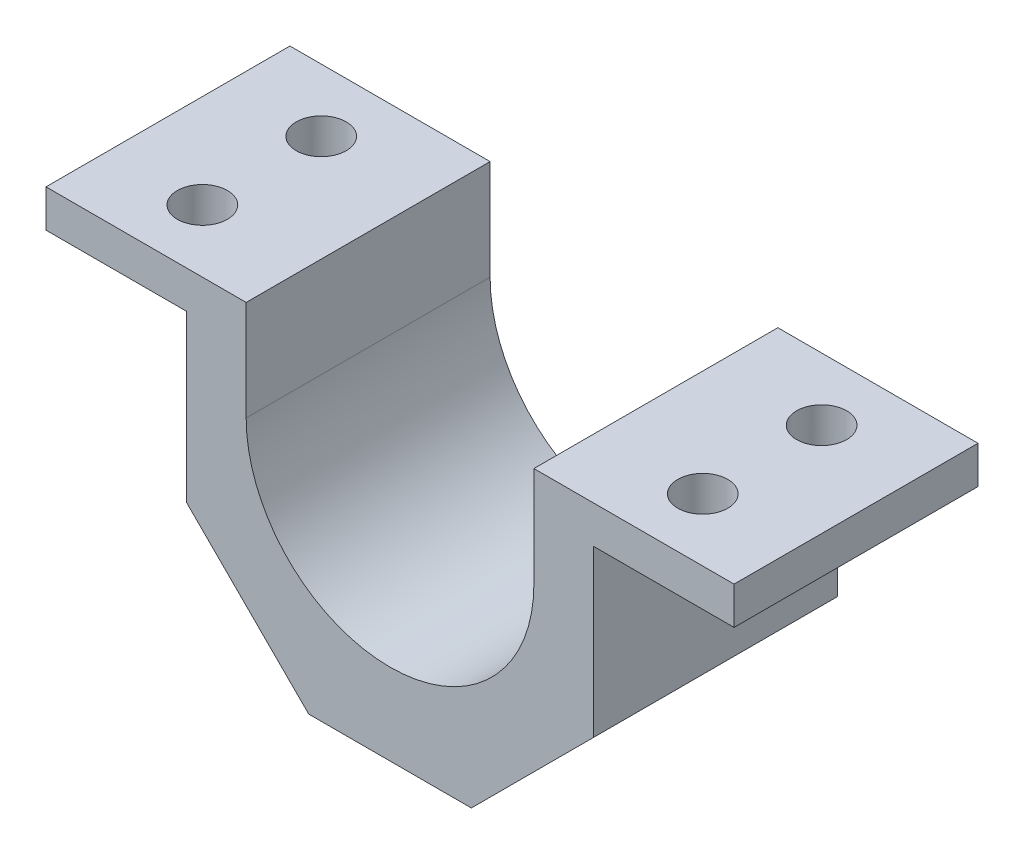
SolidWorks part; units mm, degrees
ref_plane "Front Plane" through (0, 0, 0) normal (0, 0, 1) x (1, 0, 0)
ref_plane "Top Plane" through (0, 0, 0) normal (0, 1, 0) x (1, 0, 0)
ref_plane "Right Plane" through (0, 0, 0) normal (1, 0, 0) x (0, 0, -1)
sketch "Sketch1" plane through (0, 0, 0) normal (0, 0, 1) x (1, 0, 0)
  line L0 (0, -73.4149) -> (0, 69.1816) construction
  line L4 (55, 10) -> (32.5, 10)
  line L5 (32.5, 10) -> (32.5, -16.5)
  line L6 (32.5, -16.5) -> (13, -36)
  line L7 (13, -36) -> (-13, -36)
  line L8 (-32.5, -16.5) -> (-13, -36)
  line L9 (-32.5, 10) -> (-32.5, -16.5)
  line L10 (-55, 16) -> (-55, 10)
  line L11 (-55, 10) -> (-32.5, 10)
  line L12 (-23, 16) -> (-55, 16)
  line L13 (-23, 0) -> (-23, 16)
  line L14 (55, 16) -> (55, 10)
  line L15 (23, 0) -> (23, 16)
  line L16 (23, 16) -> (55, 16)
  arc A0 (-23, 0) -> (23, 0) centre (0, 0) ccw
  point P1 (32.5, -3.25)
  point P14 (0, -36)
  point P20 (-32.5, 7.65)
  point P21 (-23, 48.9061)
  point P22 (-23, 48.9061)
  point P23 (0, 0)
  point P24 (0, 0)
  point P25 (0, 0)
  point P26 (23, 16)
  point P27 (23, 8)
  dimension "D1" = 23
  dimension "D2" = 26
  dimension "D3" = 45
  dimension "D4" = 65
  dimension "D5" = 16
  dimension "D6" = 6
  dimension "D7" = 52
  dimension "D8" = 46
  dimension "D9" = 110
extrude "Boss-Extrude1" add sketch "Sketch1" along normal mid plane 39
sketch "Sketch2" plane through (0, 16, 0) normal (0, 1, 0) x (1, 0, 0)
  line L0 (0, -19.5) -> (0, 19.5) construction
  line L1 (-23, -19.5) -> (23, -19.5) construction
  line L2 (23, 19.5) -> (-23, 19.5) construction
  line L3 (-55, 0) -> (55, 0) construction
  line L4 (-55, -19.5) -> (-55, 19.5) construction
  line L5 (55, -19.5) -> (55, 19.5) construction
  circle A0 centre (-40, -9.5) radius 4
  circle A1 centre (-40, 9.5) radius 4
  circle A2 centre (40, -9.5) radius 4
  circle A3 centre (40, 9.5) radius 4
  point P16 (-40, 13.5)
  dimension "D1" = 8
  dimension "D2" = 19
  dimension "D3" = 80
extrude "Cut-Extrude1" cut sketch "Sketch2" against normal through all
